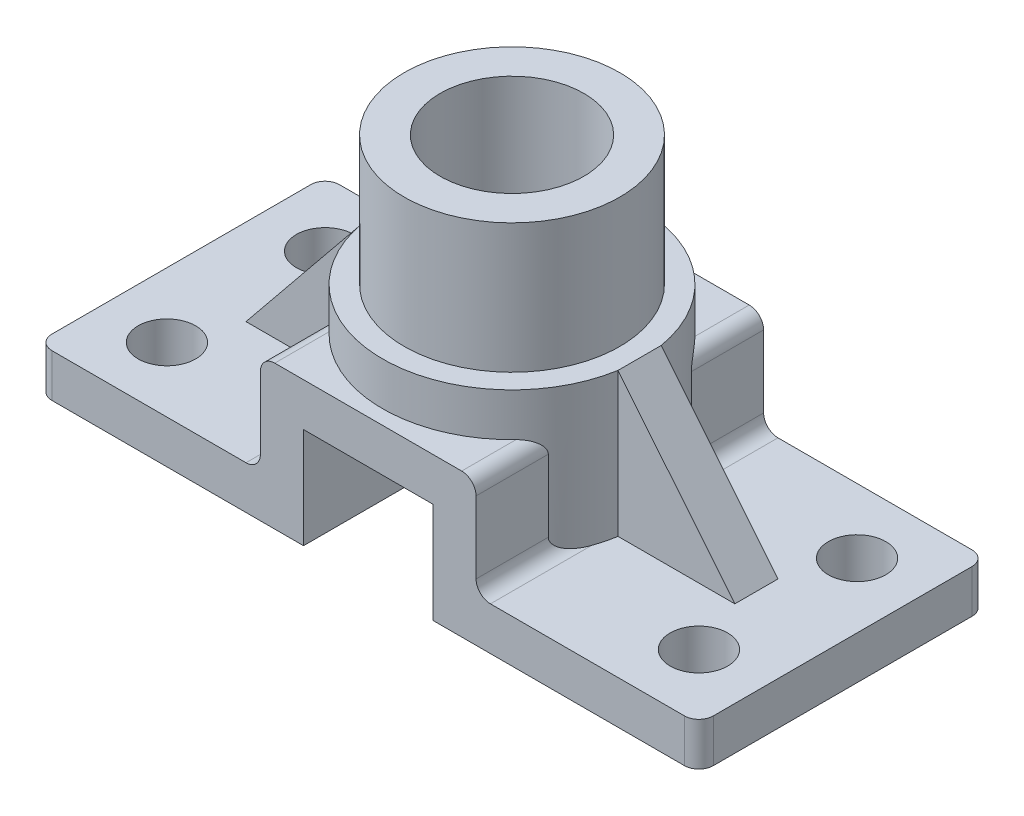
SolidWorks part; units mm, degrees
ref_plane "Ön Düzlem" through (0, 0, 0) normal (0, 0, 1) x (1, 0, 0)
ref_plane "Üst Düzlem" through (0, 0, 0) normal (0, 1, 0) x (1, 0, 0)
ref_plane "Sağ Düzlem" through (0, 0, 0) normal (1, 0, 0) x (0, 0, -1)
sketch "Çizim1" plane through (0, 0, 0) normal (0, 0, 1) x (1, 0, 0)
  line L0 (-43.1724, 26.6109) -> (-6.1724, 26.6109)
  line L21 (-6.1724, 26.6109) -> (-6.1724, 40.6109)
  line L22 (-6.1724, 40.6109) -> (11.8276, 40.6109)
  line L23 (11.8276, 40.6109) -> (11.8276, 26.6109)
  line L24 (11.8276, 26.6109) -> (48.8276, 26.6109)
  line L25 (48.8276, 26.6109) -> (48.8276, 32.6109)
  line L26 (48.8276, 32.6109) -> (17.8276, 32.6109)
  line L27 (17.8276, 32.6109) -> (17.8276, 46.6109)
  line L28 (17.8276, 46.6109) -> (-12.1724, 46.6109)
  line L29 (-12.1724, 46.6109) -> (-12.1724, 32.6109)
  line L30 (-12.1724, 32.6109) -> (-43.1724, 32.6109)
  line L32 (-43.1724, 26.6109) -> (-43.1724, 32.6109)
  dimension "D1" = 18
  dimension "D2" = 14
  dimension "D3" = 14
  dimension "D4" = 6
  dimension "D5" = 6
  dimension "D6" = 37
  dimension "D7" = 6
  dimension "D8" = 6
  dimension "D9" = 37
  dimension "D10" = 6
extrude "Yükseklik-Ekstrüzyon1" add sketch "Çizim1" along normal blind 40
fillet "Radyus1" radius 2 2 edges at (17.8276, 46.6109, 20) (-12.1724, 46.6109, 20)
fillet "Radyus2" radius 2 2 edges at (17.8276, 32.6109, 20) (-12.1724, 32.6109, 20)
fillet "Radyus4" radius 2 3 edges at (48.8276, 29.6109, 40) (-43.1724, 29.6109, 40) (-43.1724, 29.6109, 0)
fillet "Radyus5" radius 2 1 edges at (48.8276, 29.6109, 0)
sketch "Çizim5" plane through (0, 32.6109, 0) normal (0, 1, 0) x (1, 0, 0)
  line L0 (46.8276, -40) -> (19.8276, -40) construction
  line L1 (48.8276, -38) -> (48.8276, -2) construction
  line L2 (46.8276, 0) -> (19.8276, 0) construction
  line L3 (-14.1724, 0) -> (-41.1724, 0) construction
  line L4 (-43.1724, -38) -> (-43.1724, -2) construction
  line L5 (-14.1724, -40) -> (-41.1724, -40) construction
  circle A0 centre (-34.1724, -9) radius 4
  circle A1 centre (-34.1724, -31) radius 4
  circle A2 centre (39.8276, -9) radius 4
  circle A3 centre (39.8276, -31) radius 4
  dimension "D1" = 8
  dimension "D2" = 8
  dimension "D3" = 8
  dimension "D4" = 8
  dimension "D5" = 9
  dimension "D6" = 9
  dimension "D7" = 9
  dimension "D8" = 9
  dimension "D9" = 9
  dimension "D10" = 9
  dimension "D11" = 9
  dimension "D12" = 9
extrude "Kes-Ekstrüzyon1" cut sketch "Çizim5" against normal through all
ref_plane "Düzlem1" through (0, 52.6109, 0) normal (0, 1, 0) x (1, 0, 0)
sketch "Çizim7" plane through (0, 52.6109, 0) normal (0, 1, 0) x (1, 0, 0)
  line L0 (15.8276, 0) -> (-10.1724, 0) construction
  line L1 (-43.1724, -38) -> (-43.1724, -2) construction
  circle A0 centre (2.8276, -20) radius 18
  dimension "D1" = 36
  dimension "D2" = 20
  dimension "D3" = 46
extrude "Yükseklik-Ekstrüzyon3" add sketch "Çizim7" against normal up to next
sketch "Çizim8" plane through (0, 52.6109, 0) normal (0, 1, 0) x (1, 0, 0)
  circle A0 centre (2.8276, -20) radius 15
  circle A1 centre (2.8276, -20) radius 10
  dimension "D1" = 30
  dimension "D2" = 20
extrude "Yükseklik-Ekstrüzyon4" add sketch "Çizim8" along normal blind 18
sketch "Çizim9" plane through (0, 52.6109, 0) normal (0, 1, 0) x (1, 0, 0)
  circle A0 centre (2.8276, -20) radius 7.5
  dimension "D1" = 15
extrude "Kes-Ekstrüzyon3" cut sketch "Çizim9" against normal through all contours A0
sketch "Çizim12" plane through (-12.1724, 0, 0) normal (-1, 0, 0) x (0, 0, 1)
  line L0 (15.95, 52.6109) -> (-15.95, 52.6109) construction
  line L1 (17, 52.6109) -> (23, 52.6109)
  line L2 (17, 52.6109) -> (17, 32.6109)
  line L3 (17, 32.6109) -> (23, 32.6109)
  line L4 (23, 52.6109) -> (23, 32.6109)
  line L5 (38, 32.6109) -> (2, 32.6109) construction
  line L6 (0, 44.6109) -> (0, 34.6109) construction
  dimension "D1" = 6
  dimension "D2" = 17
extrude "Yükseklik-Ekstrüzyon5" add sketch "Çizim12" along normal blind 19
sketch "Çizim13" plane through (17.8276, 0, 0) normal (1, 0, 0) x (0, 0, -1)
  line L0 (15.95, 52.6109) -> (-15.95, 52.6109) construction
  line L1 (-23, 52.6109) -> (-17, 52.6109)
  line L2 (-23, 52.6109) -> (-23, 32.6109)
  line L3 (-23, 32.6109) -> (-17, 32.6109)
  line L4 (-17, 52.6109) -> (-17, 32.6109)
  line L5 (-38, 32.6109) -> (-2, 32.6109) construction
  line L6 (-40, 34.6109) -> (-40, 44.6109) construction
  point P8 (-23, 42.6109)
  dimension "D1" = 6
  dimension "D2" = 17
extrude "Yükseklik-Ekstrüzyon6" add sketch "Çizim13" along normal blind 19
sketch "Çizim14" plane through (0, 0, 23) normal (0, 0, 1) x (1, 0, 0)
  line L0 (-14.9207, 52.6109) -> (-31.1724, 32.6109)
  line L1 (-14.9207, 52.6109) -> (-34.8394, 68.7966)
  line L2 (-31.1724, 32.6109) -> (-51.0912, 48.7966)
  line L3 (-34.8394, 68.7966) -> (-51.0912, 48.7966)
  line L4 (20.5758, 52.6109) -> (36.8276, 32.6109)
  line L5 (20.5758, 52.6109) -> (42.7926, 70.664)
  line L6 (36.8276, 32.6109) -> (59.0444, 50.664)
  line L7 (42.7926, 70.664) -> (59.0444, 50.664)
  line L8 (15.95, 52.6109) -> (-15.95, 52.6109) construction
  line L9 (36.8276, 52.6109) -> (36.8276, 32.6109) construction
  line L10 (46.8276, 32.6109) -> (19.8276, 32.6109) construction
extrude "Kes-Ekstrüzyon4" cut sketch "Çizim14" against normal through all contours L0 L1 L3 L2 | L4 L5 L7 L6
